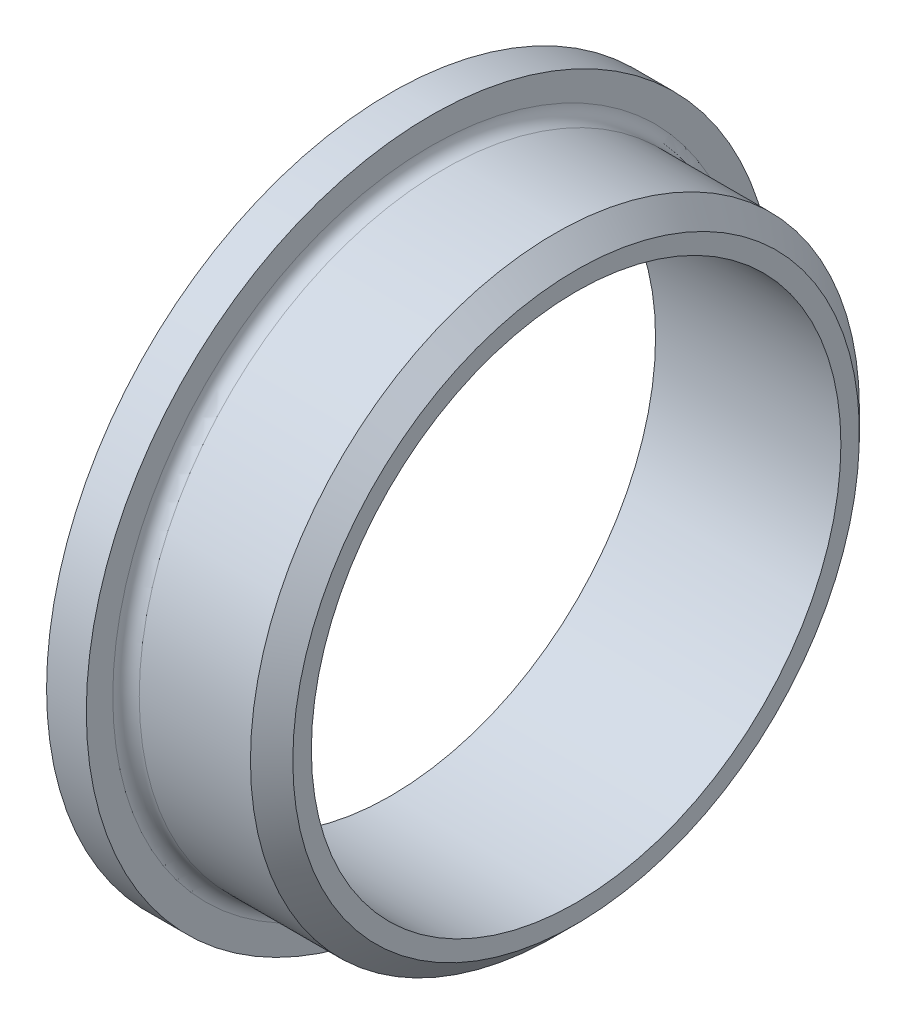
SolidWorks part; units mm, degrees
material "PPS"
ref_plane "Front Plane" through (0, 0, 0) normal (0, 0, 1) x (1, 0, 0)
ref_plane "Top Plane" through (0, 0, 0) normal (0, 1, 0) x (1, 0, 0)
ref_plane "Right Plane" through (0, 0, 0) normal (1, 0, 0) x (0, 0, -1)
sketch "Sketch1" plane through (0, 0, 0) normal (0, 0, 1) x (1, 0, 0)
  line L0 (0, 0) -> (22.3478, 0) construction
  line L1 (7, 10) -> (0, 10)
  line L2 (0, 10) -> (0, 13)
  line L3 (0, 13) -> (1.5, 13)
  line L4 (1.5, 13) -> (1.5, 11.5)
  line L5 (1.5, 11.5) -> (7, 11.5)
  line L6 (7, 11.5) -> (7, 10)
  point P9 (0, 11.5)
  dimension "D1" = 10
  dimension "D2" = 11.5
  dimension "D3" = 13
  dimension "D4" = 7
  dimension "D5" = 1.5
revolve "Revolve1" add sketch "Sketch1" angle 360 about L0
fillet "Fillet1" radius 0.5 1 edges at (1.5, 0, 11.5)
chamfer "Chamfer1" distance 0.8 angle 45 1 edges at (7, 0, 11.5)
